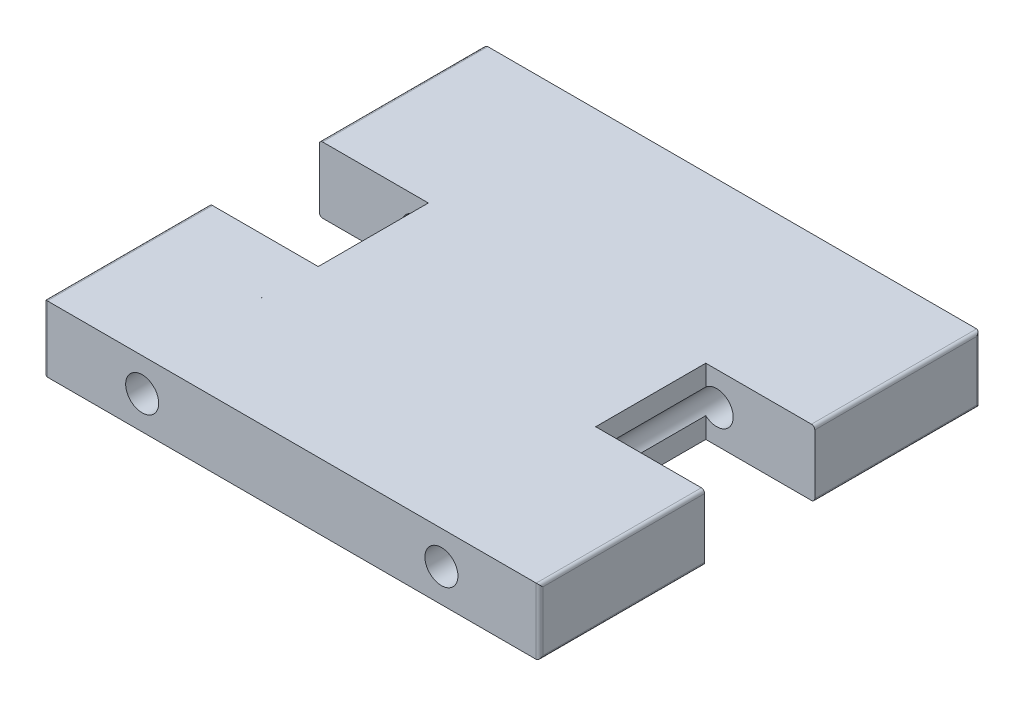
SolidWorks part; units mm, degrees
ref_plane "Piano frontale" through (0, 0, 0) normal (0, 0, 1) x (1, 0, 0)
ref_plane "Piano superiore" through (0, 0, 0) normal (0, 1, 0) x (1, 0, 0)
ref_plane "Piano destro" through (0, 0, 0) normal (1, 0, 0) x (0, 0, -1)
sketch "Schizzo1" plane through (0, 0, 0) normal (0, 1, 0) x (1, 0, 0)
  line L1 (3, 0) -> (447, 0)
  line L2 (0, 3) -> (0, 397)
  line L3 (3, 400) -> (447, 400)
  line L4 (450, 3) -> (450, 397)
  arc A0 (447, 400) -> (450, 397) centre (447, 397) cw
  arc A1 (447, 0) -> (450, 3) centre (447, 3) ccw
  arc A2 (3, 0) -> (0, 3) centre (3, 3) cw
  arc A3 (0, 397) -> (3, 400) centre (3, 397) cw
  point P7 (450, 400)
  point P12 (0, 0)
  point P15 (0, 400)
  dimension "D3" = 3
  dimension "D1" = 450
  dimension "D2" = 400
extrude "Estrusione-Estrusione1" add sketch "Schizzo1" along normal blind 60
sketch "Schizzo3" plane through (0, 0, 0) normal (0, 0, 1) x (1, 0, 0)
  line L0 (3, 60) -> (447, 60)
  line L1 (450, 57) -> (450, 3)
  line L2 (447, 0) -> (3, 0)
  line L3 (0, 3) -> (0, 57)
  line L4 (0, 30) -> (450, 30) construction
  line L5 (225, 60) -> (225, 0) construction
  arc A0 (447, 60) -> (450, 57) centre (447, 57) cw
  arc A1 (450, 3) -> (447, 0) centre (447, 3) cw
  arc A2 (3, 0) -> (0, 3) centre (3, 3) cw
  arc A3 (3, 60) -> (0, 57) centre (3, 57) ccw
  circle A4 centre (89.1, 30) radius 15
  circle A5 centre (360.9, 30) radius 15
  point P11 (450, 60)
  point P14 (450, 0)
  point P17 (0, 0)
  point P20 (0, 60)
  dimension "D1" = 3
  dimension "D2" = 30
  dimension "D3" = 30
  dimension "D4" = 271.8
  dimension "D5" = 135.9
extrude "Taglio-Estrusione2" cut sketch "Schizzo3" against normal through all both and the other way through all flip side to cut
sketch "Schizzo4" plane through (0, 0, 0) normal (0, 1, 0) x (1, 0, 0)
  line L0 (0, 200) -> (450, 200) construction
  line L1 (0, 397) -> (0, 3) construction
  line L2 (450, 397) -> (450, 3) construction
  line L4 (-1, 250) -> (99, 250)
  line L5 (-1, 250) -> (-1, 150)
  line L6 (-1, 150) -> (99, 150)
  line L7 (99, 250) -> (99, 150)
  line L8 (351, 250) -> (451, 250)
  line L9 (351, 250) -> (351, 150)
  line L10 (351, 150) -> (451, 150)
  line L11 (451, 250) -> (451, 150)
  dimension "D1" = 100
  dimension "D2" = 100
  dimension "D3" = 50
  dimension "D4" = 100
  dimension "D5" = 100
  dimension "D6" = 50
  dimension "D7" = 1
  dimension "D8" = 1
extrude "Taglio-Estrusione3" cut sketch "Schizzo4" along normal through all
